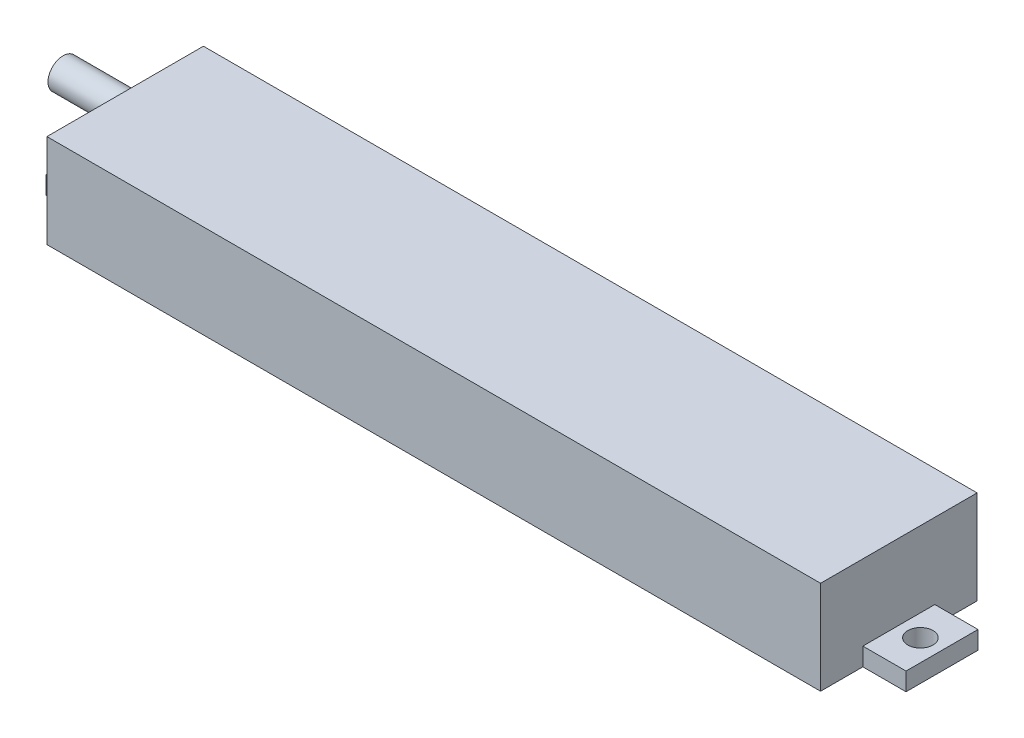
SolidWorks part; units mm, degrees
ref_plane "正面" through (0, 0, 0) normal (0, 0, 1) x (1, 0, 0)
ref_plane "平面" through (0, 0, 0) normal (0, 1, 0) x (1, 0, 0)
ref_plane "右側面" through (0, 0, 0) normal (1, 0, 0) x (0, 0, -1)
sketch "ｽｹｯﾁ1" plane through (0, 0, 0) normal (0, 1, 0) x (1, 0, 0)
  line L1 (-107.5, 21.75) -> (107.5, 21.75)
  line L2 (-107.5, 21.75) -> (-107.5, -21.75)
  line L3 (-107.5, -21.75) -> (107.5, -21.75)
  line L4 (107.5, 21.75) -> (107.5, -21.75)
  point P4 (0, 21.75)
  point P6 (-107.5, 0)
  dimension "D1" = 43.5
  dimension "D2" = 215
extrude "ﾎﾞｽ - 押し出し1" add sketch "ｽｹｯﾁ1" along normal blind 26
sketch "ｽｹｯﾁ2" plane through (0, 0, 0) normal (0, -1, 0) x (1, 0, 0)
  line L0 (0, -21.75) -> (0, 21.75) construction
  line L1 (-119.5, -10) -> (-107.5, -10)
  line L2 (-119.5, -10) -> (-119.5, 10)
  line L3 (-119.5, 10) -> (-107.5, 10)
  line L4 (-107.5, -10) -> (-107.5, 10)
  line L5 (107.5, -21.75) -> (-107.5, -21.75) construction
  line L6 (-107.5, 21.75) -> (107.5, 21.75) construction
  line L7 (-107.5, -21.75) -> (-107.5, 21.75) construction
  line L8 (107.5, -10) -> (107.5, 10)
  line L9 (119.5, 10) -> (107.5, 10)
  line L10 (119.5, -10) -> (119.5, 10)
  line L11 (119.5, -10) -> (107.5, -10)
  circle A0 centre (-113.5, 0) radius 3.5
  circle A1 centre (113.5, 0) radius 3.5
  point P12 (-119.5, 0)
  point P17 (-113.5, 10)
  dimension "D3" = 7
  dimension "D1" = 12
  dimension "D2" = 20
extrude "ﾎﾞｽ - 押し出し2" add sketch "ｽｹｯﾁ2" against normal blind 5
sketch "ｽｹｯﾁ3" plane through (-107.5, 0, 0) normal (-1, 0, 0) x (0, 0, 1)
  line L0 (-21.75, 26) -> (-21.75, 0) construction
  line L1 (-21.75, 26) -> (21.75, 26) construction
  circle A0 centre (-7.75, 14) radius 4.2
  dimension "D1" = 14
  dimension "D3" = 8.4
  dimension "D2" = 12
extrude "ﾎﾞｽ - 押し出し3" add sketch "ｽｹｯﾁ3" along normal blind 25
sketch "ｽｹｯﾁ4" plane through (0, 0, 0) normal (0, -1, 0) x (1, 0, 0)
  line L0 (-113.5, 0) -> (113.5, 0) construction
  line L1 (-120, -15) -> (120, -15) construction
  line L2 (-120, -15) -> (-120, 15) construction
  line L3 (-120, 15) -> (120, 15) construction
  line L4 (120, -15) -> (120, 15) construction
  line L6 (-126, -22) -> (126, -22)
  line L7 (-126, -22) -> (-126, 22)
  line L8 (-126, 22) -> (126, 22)
  line L9 (126, -22) -> (126, 22)
  circle A0 centre (-120, -15) radius 2.25
  circle A1 centre (-120, 15) radius 2.25
  circle A2 centre (120, 15) radius 2.25
  circle A3 centre (120, -15) radius 2.25
  circle A4 centre (-113.5, 0) radius 2.9
  circle A5 centre (113.5, 0) radius 2.9
  point P8 (120, 0)
  point P9 (0, -15)
  point P14 (-126, 0)
  point P16 (0, -22)
  dimension "D3" = 4.5
  dimension "D6" = 5.8
  dimension "D1" = 240
  dimension "D2" = 30
  dimension "D4" = 7
  dimension "D5" = 6
  dimension "D7" = 44
extrude "ﾎﾞｽ - 押し出し4" [suppressed] add sketch "ｽｹｯﾁ4" along normal blind 6.5 separate body
fillet "ﾌｨﾚｯﾄ1" [suppressed] radius 3
